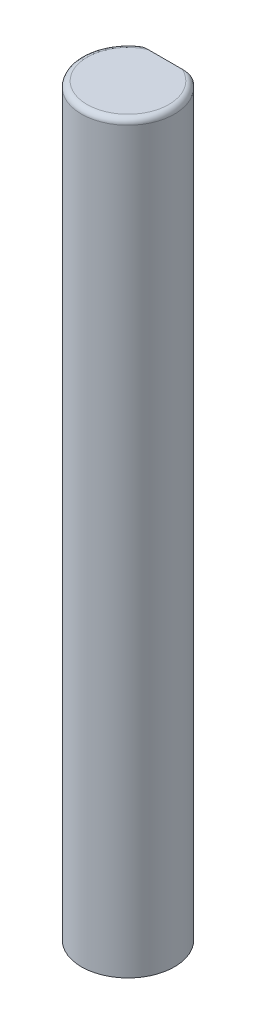
SolidWorks part; units mm, degrees
ref_plane "Front Plane" through (0, 0, 0) normal (0, 0, 1) x (1, 0, 0)
ref_plane "Top Plane" through (0, 0, 0) normal (0, 1, 0) x (1, 0, 0)
ref_plane "Right Plane" through (0, 0, 0) normal (1, 0, 0) x (0, 0, -1)
sketch "Sketch1" plane through (0, 0, 0) normal (0, 1, 0) x (1, 0, 0)
  circle A0 centre (0, 0) radius 2.5
  dimension "D1" = 5
extrude "Boss-Extrude1" add sketch "Sketch1" along normal blind 40
sketch "Sketch2" plane through (0, 40, 0) normal (0, 1, 0) x (1, 0, 0)
  line L1 (-4.1803, 2) -> (4.0513, 2)
  line L2 (-4.1803, 2) -> (-4.1803, 4.4772)
  line L3 (-4.1803, 4.4772) -> (4.0513, 4.4772)
  line L4 (4.0513, 2) -> (4.0513, 4.4772)
  circle A0 centre (0, 0) radius 2.5 construction
  dimension "D1" = 2
  dimension "D4" = 4.1803
  dimension "D2" = 2.4772
  dimension "D3" = 8.2316
extrude "Cut-Extrude1" cut sketch "Sketch2" against normal blind 18
fillet "Fillet1" radius 0.3 1 edges at (0, 40, 2.5)
